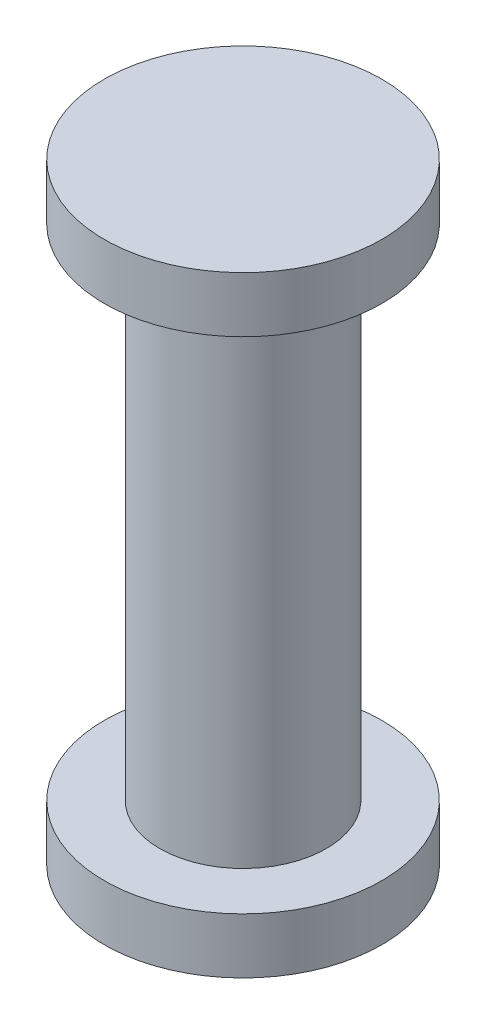
SolidWorks part; units mm, degrees
material "1023 Листовая углеродистая сталь (SS)"
ref_plane "Спереди" through (0, 0, 0) normal (0, 0, 1) x (1, 0, 0)
ref_plane "Сверху" through (0, 0, 0) normal (0, 1, 0) x (1, 0, 0)
ref_plane "Справа" through (0, 0, 0) normal (1, 0, 0) x (0, 0, -1)
sketch "Эскиз1" plane through (0, 0, 0) normal (0, 0, 1) x (1, 0, 0)
  line L0 (0, 0) -> (0, 11)
  line L1 (0, 11) -> (-2.5, 11)
  line L3 (-1.5, 10) -> (-1.5, 1)
  line L4 (-1.5, 1) -> (-2.5, 1)
  line L5 (-2.5, 1) -> (-2.5, 0)
  line L6 (-2.5, 0) -> (0, 0)
  line L7 (-2.5, 11) -> (-2.5, 10)
  line L8 (-2.5, 10) -> (-1.5, 10)
  dimension "D1" = 11
  dimension "D2" = 1
  dimension "D3" = 2.5
  dimension "D4" = 1.5
revolve "Повернуть1" add sketch "Эскиз1" angle 360 about L0
scale "Масштаб1" scale about centroid uniform scaling yes scale factor 2.2
equation "\"Scale\"= 1"
